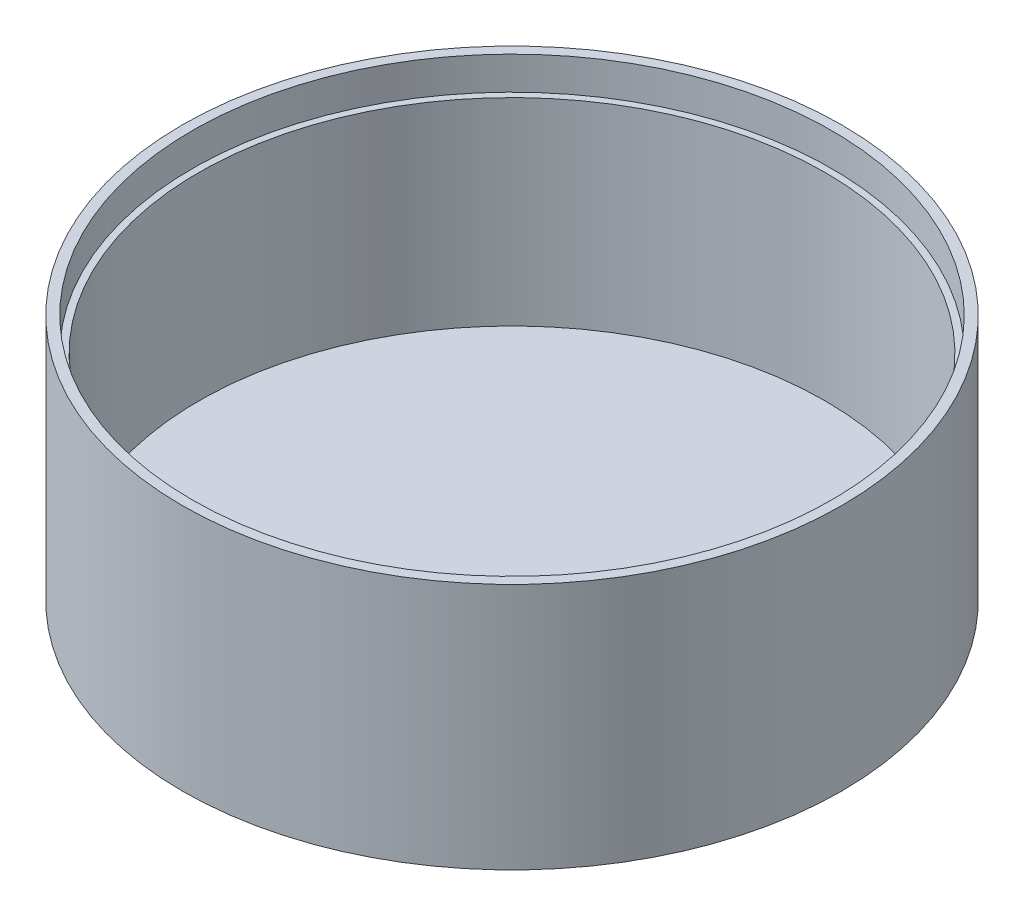
SolidWorks part; units mm, degrees
ref_plane "Front Plane" through (0, 0, 0) normal (0, 0, 1) x (1, 0, 0)
ref_plane "Top Plane" through (0, 0, 0) normal (0, 1, 0) x (1, 0, 0)
ref_plane "Right Plane" through (0, 0, 0) normal (1, 0, 0) x (0, 0, -1)
sketch "Sketch1" plane through (0, 0, 0) normal (0, 1, 0) x (1, 0, 0)
  circle A0 centre (0, 0) radius 40
extrude "Boss-Extrude1" add sketch "Sketch1" along normal blind 30
shell "Shell1" thickness 2
sketch "Sketch2" plane through (0, 30, 0) normal (0, 1, 0) x (1, 0, 0)
  circle A0 centre (0, 0) radius 38.8
extrude "Cut-Extrude1" cut sketch "Sketch2" against normal blind 4
